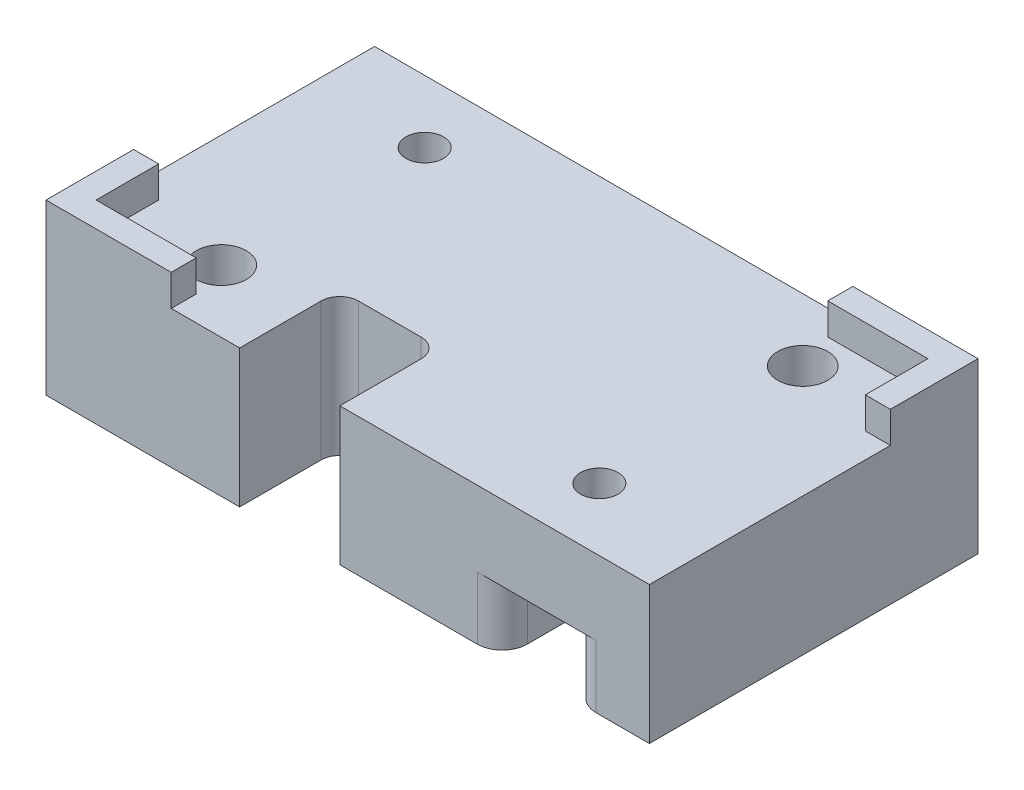
SolidWorks part; units mm, degrees
ref_plane "Front Plane" through (0, 0, 0) normal (0, 0, 1) x (1, 0, 0)
ref_plane "Top Plane" through (0, 0, 0) normal (0, 1, 0) x (1, 0, 0)
ref_plane "Right Plane" through (0, 0, 0) normal (1, 0, 0) x (0, 0, -1)
sketch "Sketch1" plane through (0, 0, 0) normal (0, 1, 0) x (1, 0, 0)
  line L0 (-24.1, 13.125) -> (24.1, -13.125) construction
  line L1 (-24.1, 13.125) -> (24.1, 13.125)
  line L2 (-24.1, 13.125) -> (-24.1, -13.125)
  line L3 (-24.1, -13.125) -> (24.1, -13.125)
  line L4 (24.1, 13.125) -> (24.1, -13.125)
  line L5 (0, 10.625) -> (0, 13.125) construction
  line L6 (-21.6, 10.625) -> (21.6, 10.625) construction
  line L7 (-21.6, 10.625) -> (-21.6, -10.625) construction
  line L8 (-21.6, -10.625) -> (21.6, -10.625) construction
  line L9 (21.6, 10.625) -> (21.6, -10.625) construction
  line L10 (21.6, 0) -> (24.1, 0) construction
  line L11 (-15.1, 8.125) -> (-15.1, 10.625) construction
  line L12 (-15.1, 8.125) -> (-21.6, 8.125) construction
  line L13 (15.1, -8.125) -> (21.6, -8.125) construction
  line L14 (15.1, -8.125) -> (15.1, -10.625) construction
  circle A0 centre (-15.1, 8.125) radius 1.5
  circle A1 centre (15.1, -8.125) radius 1.5
  circle A2 centre (-15.1, -8.125) radius 2
  circle A3 centre (15.1, 8.125) radius 2
  dimension "D4" = 3
  dimension "D7" = 4
  dimension "D1" = 43.2
  dimension "D2" = 21.25
  dimension "D3" = 2.5
  dimension "D5" = 6.5
  dimension "D6" = 2.5
extrude "Boss-Extrude1" add sketch "Sketch1" along normal blind 11
sketch "Sketch2" plane through (0, 11, 0) normal (0, 1, 0) x (1, 0, 0)
  line L8 (-24.1, -6.125) -> (-22.1, -6.125)
  line L9 (-24.1, 13.125) -> (-24.1, -13.125) construction
  line L10 (-22.1, -6.125) -> (-22.1, -11.125)
  line L11 (-22.1, -11.125) -> (-14.1, -11.125)
  line L12 (-14.1, -11.125) -> (-14.1, -13.125)
  line L13 (-24.1, -13.125) -> (24.1, -13.125) construction
  line L14 (-14.1, -13.125) -> (-24.1, -13.125)
  line L15 (-24.1, -13.125) -> (-24.1, -6.125)
  line L16 (14.1, 13.125) -> (14.1, 11.125)
  line L17 (24.1, 13.125) -> (-24.1, 13.125) construction
  line L18 (14.1, 11.125) -> (22.1, 11.125)
  line L19 (22.1, 11.125) -> (22.1, 6.125)
  line L20 (22.1, 6.125) -> (24.1, 6.125)
  line L21 (24.1, -13.125) -> (24.1, 13.125) construction
  line L22 (24.1, 6.125) -> (24.1, 13.125)
  line L23 (24.1, 13.125) -> (14.1, 13.125)
  dimension "D1" = 8
  dimension "D2" = 5
  dimension "D3" = 2
extrude "Boss-Extrude2" add sketch "Sketch2" along normal blind 2.5
sketch "Sketch3" plane through (0, 11, 0) normal (0, 1, 0) x (1, 0, 0)
  line L0 (-14.1, -13.125) -> (24.1, -13.125) construction
  line L1 (-8.63, -5.125) -> (-0.63, -5.125)
  line L2 (-8.63, -5.125) -> (-8.63, -13.125)
  line L3 (-8.63, -13.125) -> (-0.63, -13.125)
  line L4 (-0.63, -5.125) -> (-0.63, -13.125)
  line L6 (-24.1, -6.125) -> (-24.1, -13.125) construction
  point P6 (-4.63, -5.125)
  dimension "D1" = 8
  dimension "D2" = 19.47
  dimension "D3" = 8
extrude "Cut-Extrude1" cut sketch "Sketch3" against normal through all
fillet "Fillet1" radius 1.5 2 edges at (-0.63, 5.5, 5.125) (-8.63, 5.5, 5.125)
sketch "Sketch5" plane through (0, 0, 0) normal (0, -1, 0) x (1, 0, 0)
  line L0 (-17.85, -9.7127) -> (-17.85, -13.125)
  line L1 (-15.1, -4.9496) -> (-17.85, -6.5373)
  line L2 (-17.85, -6.5373) -> (-17.85, -9.7127)
  line L3 (-17.85, -9.7127) -> (-15.1, -11.3004) construction
  line L4 (-15.1, -11.3004) -> (-12.35, -9.7127) construction
  line L5 (-12.35, -9.7127) -> (-12.35, -6.5373)
  line L6 (-12.35, -6.5373) -> (-15.1, -4.9496)
  line L7 (15.1, 4.9496) -> (17.85, 6.5373)
  line L8 (17.85, 6.5373) -> (17.85, 9.7127)
  line L9 (17.85, 9.7127) -> (15.1, 11.3004) construction
  line L10 (15.1, 11.3004) -> (12.35, 9.7127) construction
  line L11 (12.35, 9.7127) -> (12.35, 6.5373)
  line L12 (12.35, 6.5373) -> (15.1, 4.9496)
  line L13 (24.1, -13.125) -> (-24.1, -13.125) construction
  line L14 (-17.85, -13.125) -> (-12.35, -13.125)
  line L15 (-12.35, -13.125) -> (-12.35, -9.7127)
  line L16 (12.35, 9.7127) -> (12.35, 13.125)
  line L17 (-0.63, 13.125) -> (24.1, 13.125) construction
  line L18 (12.35, 13.125) -> (17.85, 13.125)
  line L19 (17.85, 13.125) -> (17.85, 9.7127)
  circle A0 centre (-15.1, -8.125) radius 2.75 construction
  circle A1 centre (15.1, 8.125) radius 2.75 construction
  dimension "D1" = 5.5
extrude "Cut-Extrude2" cut sketch "Sketch5" against normal blind 5
fillet "Fillet2" radius 2 4 edges at (-12.35, 2.5, -13.125) (-17.85, 2.5, -13.125) (17.85, 2.5, 13.125) (12.35, 2.5, 13.125)
